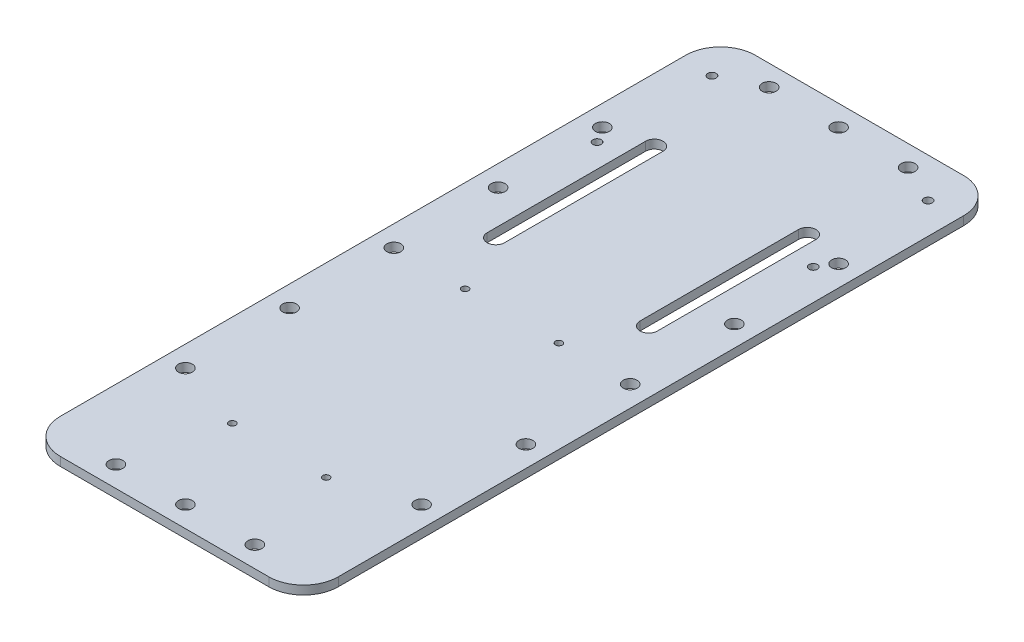
SolidWorks part; units mm, degrees
material "Thornel Mat VMA"
ref_plane "Front Plane" through (0, 0, 0) normal (0, 0, 1) x (1, 0, 0)
ref_plane "Top Plane" through (0, 0, 0) normal (0, 1, 0) x (1, 0, 0)
ref_plane "Right Plane" through (0, 0, 0) normal (1, 0, 0) x (0, 0, -1)
sketch "Sketch1" plane through (0, 0, 0) normal (0, 1, 0) x (1, 0, 0)
  line L0 (-157.6996, 42.9503) -> (197.9004, 42.9503) construction
  line L1 (-30.6996, 42.9503) -> (70.9004, 42.9503)
  line L2 (-30.6996, 42.9503) -> (-30.6996, -211.0497)
  line L3 (-30.6996, -211.0497) -> (70.9004, -211.0497)
  line L4 (70.9004, 42.9503) -> (70.9004, -211.0497)
  line L5 (-157.6996, -211.0497) -> (197.9004, -211.0497) construction
  dimension "D1" = 127
  dimension "D2" = 127
  dimension "D3" = 101.6
  dimension "D4" = 254
extrude "Boss-Extrude1" add sketch "Sketch1" along normal blind 3.175
sketch "Sketch2" plane through (0, 3.175, 0) normal (0, 1, 0) x (1, 0, 0)
  line L0 (20.1004, 42.9503) -> (20.1004, -50.0615) construction
  line L1 (70.9004, 42.9503) -> (-30.6996, 42.9503) construction
  line L2 (20.1004, -84.0497) -> (37.2454, -84.0497) construction
  line L3 (20.1004, 28.5424) -> (-19.3996, 28.5424) construction
  line L4 (-30.6996, 42.9503) -> (-30.6996, -211.0497) construction
  line L5 (37.2454, -84.0497) -> (37.2454, -169.1397) construction
  line L6 (20.1004, -69.1513) -> (20.1004, -99.4755) construction
  line L7 (37.2454, -169.1397) -> (2.9554, -169.1397) construction
  line L8 (2.9554, -169.1397) -> (2.9554, -84.0497) construction
  line L9 (2.9554, -84.0497) -> (20.1004, -84.0497) construction
  line L10 (2.9554, -126.5947) -> (37.2454, -126.5947) construction
  line L12 (-19.3996, 28.5424) -> (-19.3996, -13.4576) construction
  line L13 (-19.3996, -13.4576) -> (59.6004, -13.4576) construction
  line L14 (59.6004, -13.4576) -> (59.6004, 28.5424) construction
  line L15 (59.6004, 28.5424) -> (20.1004, 28.5424) construction
  line L16 (-19.3996, 7.5424) -> (59.6004, 7.5424) construction
  circle A0 centre (-5.2996, 35.3303) radius 2.54
  circle A1 centre (20.1004, 35.3303) radius 2.54
  circle A2 centre (45.5004, 35.3303) radius 2.54
  circle A3 centre (-23.0796, -84.0497) radius 2.54
  circle A5 centre (-23.0796, -45.9497) radius 2.54
  circle A6 centre (-23.0796, -7.8497) radius 2.54
  circle A7 centre (63.2804, -7.8497) radius 2.54
  circle A8 centre (63.2804, -45.9497) radius 2.54
  circle A10 centre (63.2804, -84.0497) radius 2.54
  circle A12 centre (63.2804, -122.1497) radius 2.54
  circle A13 centre (63.2804, -160.2497) radius 2.54
  circle A14 centre (-23.0796, -160.2497) radius 2.54
  circle A15 centre (-23.0796, -122.1497) radius 2.54
  circle A17 centre (45.5004, -203.4297) radius 2.54
  circle A18 centre (20.1004, -203.4297) radius 2.54
  circle A19 centre (-5.2996, -203.4297) radius 2.54
  circle A23 centre (2.9554, -84.0497) radius 1.25
  circle A24 centre (37.2454, -84.0497) radius 1.25
  circle A25 centre (37.2454, -169.1397) radius 1.25
  circle A26 centre (2.9554, -169.1397) radius 1.25
  circle A31 centre (-19.3996, 28.5424) radius 1.524
  circle A32 centre (59.6004, 28.5424) radius 1.524
  circle A33 centre (59.6004, -13.4576) radius 1.524
  circle A34 centre (-19.3996, -13.4576) radius 1.524
  dimension "D3" = 5.08
  dimension "D4" = 5.08
  dimension "D5" = 5.08
  dimension "D10" = 5.08
  dimension "D11" = 5.08
  dimension "D12" = 5.08
  dimension "D1" = 25.4
  dimension "D2" = 25.4
  dimension "D6" = 38.1
  dimension "D8" = 38.1
  dimension "D13" = 7.62
  dimension "D14" = 7.62
extrude "Cut-Extrude1" cut sketch "Sketch2" against normal through all
fillet "Fillet1" radius 12.7 4 edges at (-30.6996, 1.5875, 211.0497) (70.9004, 1.5875, 211.0497) (70.9004, 1.5875, -42.9503) (-30.6996, 1.5875, -42.9503)
sketch "Sketch4" plane through (0, 0, 0) normal (0, 1, 0) x (1, 0, 0)
  line L0 (20.3128, 42.9503) -> (20.3128, -211.0497) construction
  line L1 (48.2528, -4.281) -> (48.2528, -62.2184) construction
  line L2 (51.4278, -4.281) -> (51.4278, -62.2184)
  line L3 (45.0778, -4.281) -> (45.0778, -62.2184)
  line L4 (-7.6272, -4.281) -> (-7.6272, -62.2184) construction
  line L5 (58.2004, 42.9503) -> (-17.9996, 42.9503) construction
  line L6 (-17.9996, -211.0497) -> (58.2004, -211.0497) construction
  line L7 (-10.8022, -4.281) -> (-10.8022, -62.2184)
  line L8 (-4.4522, -4.281) -> (-4.4522, -62.2184)
  arc A0 (51.4278, -4.281) -> (45.0778, -4.281) centre (48.2528, -4.281) ccw
  arc A1 (45.0778, -62.2184) -> (51.4278, -62.2184) centre (48.2528, -62.2184) ccw
  arc A2 (-10.8022, -4.281) -> (-4.4522, -4.281) centre (-7.6272, -4.281) cw
  arc A3 (-4.4522, -62.2184) -> (-10.8022, -62.2184) centre (-7.6272, -62.2184) cw
  point P4 (48.2528, -33.2497)
  point P15 (-7.6272, -33.2497)
  dimension "D1" = 27.94
  dimension "D2" = 76.2
  dimension "D3" = 6.35
extrude "Cut-Extrude7" cut sketch "Sketch4" along normal through all
